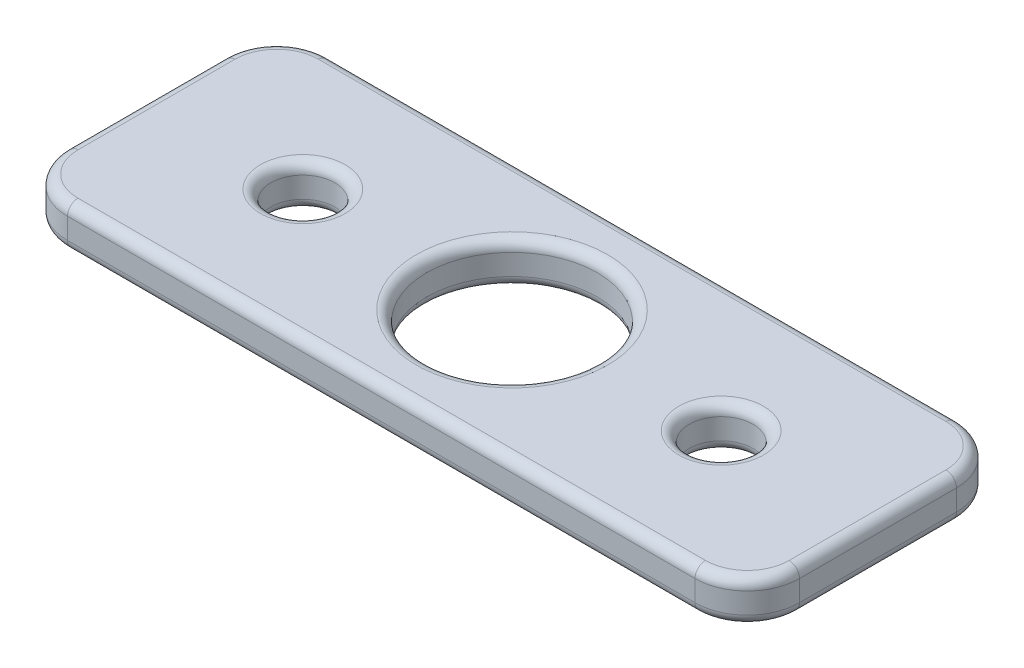
SolidWorks part; units mm, degrees
ref_plane "Front Plane" through (0, 0, 0) normal (0, 0, 1) x (1, 0, 0)
ref_plane "Top Plane" through (0, 0, 0) normal (0, 1, 0) x (1, 0, 0)
ref_plane "Right Plane" through (0, 0, 0) normal (1, 0, 0) x (0, 0, -1)
sketch "Sketch1" plane through (0, 0, 0) normal (0, 1, 0) x (1, 0, 0)
  line L0 (70, 25) -> (0, 0) construction
  line L1 (0, 0) -> (70, 0)
  line L2 (0, 0) -> (0, 25)
  line L3 (0, 25) -> (70, 25)
  line L4 (70, 0) -> (70, 25)
  line L5 (35, 12.5) -> (15, 12.5) construction
  line L6 (35, 12.5) -> (35, 25) construction
  circle A0 centre (15, 12.5) radius 3.05
  circle A1 centre (35, 12.5) radius 8.15
  circle A2 centre (55, 12.5) radius 3.05
  dimension "D3" = 6.1
  dimension "D5" = 16.3
  dimension "D1" = 70
  dimension "D2" = 25
  dimension "D4" = 20
extrude "Boss-Extrude1" add sketch "Sketch1" along normal blind 4
fillet "Fillet1" radius 5 4 edges at (70, 2, -25) (0, 2, -25) (0, 2, 0) (70, 2, 0)
fillet "Fillet2" radius 1 22 edges at (55, 0, -15.55) (15, 0, -9.45) (1.4645, 0, -23.5355) (0, 0, -12.5) (1.4645, 0, -1.4645) (35, 0, 0) (68.5355, 0, -1.4645) (70, 0, -12.5) (68.5355, 0, -23.5355) (35, 0, -25) (35, 0, -4.35) (55, 4, -15.55) (35, 4, -4.35) (15, 4, -9.45) (68.5355, 4, -1.4645) (35, 4, 0) (1.4645, 4, -1.4645) (0, 4, -12.5) (1.4645, 4, -23.5355) (35, 4, -25) (68.5355, 4, -23.5355) (70, 4, -12.5)
equation "\"centerDist\"=20.4228"
equation "\"sideWidth\"=25"
equation "\"D2@Sketch1\"=\"sideWidth\""
